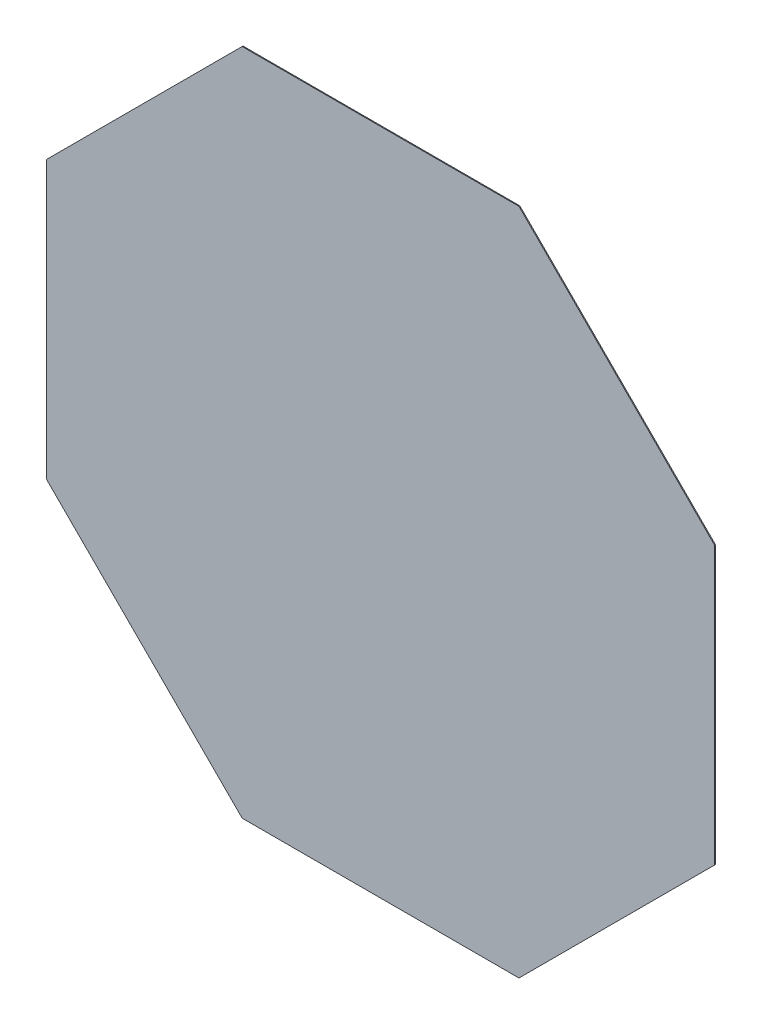
SolidWorks part; units mm, degrees
ref_plane "Front Plane" through (0, 0, 0) normal (0, 0, 1) x (1, 0, 0)
ref_plane "Top Plane" through (0, 0, 0) normal (0, 1, 0) x (1, 0, 0)
ref_plane "Right Plane" through (0, 0, 0) normal (1, 0, 0) x (0, 0, -1)
sketch "Sketch1" plane through (0, 0, 0) normal (0, 0, 1) x (1, 0, 0)
  line L14 (-10.3553, -25) -> (10.3553, -25)
  line L61 (25, 10.3553) -> (10.3553, 25)
  line L62 (10.3553, 25) -> (-10.3553, 25)
  line L63 (-10.3553, 25) -> (-25, 10.3553)
  line L64 (-25, 10.3553) -> (-25, -10.3553)
  line L65 (-25, -10.3553) -> (-10.3553, -25)
  line L67 (10.3553, -25) -> (25, -10.3553)
  line L68 (25, -10.3553) -> (25, 10.3553)
  line L69 (-10.3553, -25) -> (-5, -25) [skipped]
  circle A0 centre (0, 0) radius 25 construction
  point P0 (0, 0)
  dimension "D6" = 50
extrude "Boss-Extrude1" add sketch "Sketch1" along normal blind 0.065
